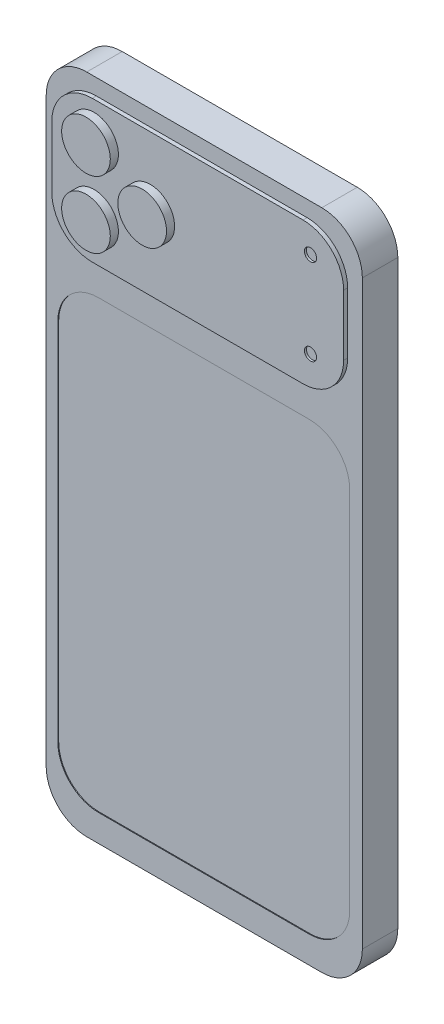
SolidWorks part; units mm, degrees
material "Plastique personnalisé"
ref_plane "Plan de face" through (0, 0, 0) normal (0, 0, 1) x (1, 0, 0)
ref_plane "Plan de dessus" through (0, 0, 0) normal (0, 1, 0) x (1, 0, 0)
ref_plane "Plan de droite" through (0, 0, 0) normal (1, 0, 0) x (0, 0, -1)
sketch "Esquisse2" plane through (0, 0, 0) normal (0, 0, 1) x (1, 0, 0)
  line L1 (10, 0) -> (68, 0)
  line L2 (0, 10) -> (0, 153.4)
  line L3 (10, 163.4) -> (68, 163.4)
  line L4 (78, 10) -> (78, 153.4)
  arc A0 (68, 0) -> (78, 10) centre (68, 10) ccw
  arc A1 (10, 0) -> (0, 10) centre (10, 10) cw
  arc A2 (0, 153.4) -> (10, 163.4) centre (10, 153.4) cw
  arc A3 (68, 163.4) -> (78, 153.4) centre (68, 153.4) cw
  point P7 (78, 0)
  point P10 (0, 0)
  point P13 (0, 163.4)
  dimension "D3" = 10
  dimension "D1" = 163.4
  dimension "D2" = 78
extrude "Boss.-Extru.1" add sketch "Esquisse2" along normal blind 8.75
sketch "Esquisse4" plane through (0, 0, 8.75) normal (0, 0, 1) x (1, 0, 0)
  line L1 (12.3759, 159.4654) -> (64.3759, 159.4654)
  line L2 (2.3759, 149.4654) -> (2.3759, 134.4654)
  line L3 (12.3759, 124.4654) -> (64.3759, 124.4654)
  line L4 (74.3759, 149.4654) -> (74.3759, 134.4654)
  arc A0 (64.3759, 124.4654) -> (74.3759, 134.4654) centre (64.3759, 134.4654) ccw
  arc A1 (64.3759, 159.4654) -> (74.3759, 149.4654) centre (64.3759, 149.4654) cw
  arc A2 (12.3759, 159.4654) -> (2.3759, 149.4654) centre (12.3759, 149.4654) ccw
  arc A3 (2.3759, 134.4654) -> (12.3759, 124.4654) centre (12.3759, 134.4654) ccw
  point P8 (74.3759, 159.4654)
  point P11 (2.3759, 159.4654)
  point P14 (2.3759, 124.4654)
  dimension "D3" = 10
  dimension "D1" = 72
  dimension "D2" = 35
extrude "Boss.-Extru.2" add sketch "Esquisse4" along normal blind 1
sketch "Esquisse5" plane through (0, 0, 9.75) normal (0, 0, 1) x (1, 0, 0)
  circle A0 centre (12.8176, 150.6803) radius 6
  circle A1 centre (26.6807, 142.2325) radius 6
  circle A2 centre (12.8176, 134.2179) radius 6
  dimension "D1" = 12
  dimension "D2" = 12
  dimension "D3" = 12
extrude "Boss.-Extru.3" add sketch "Esquisse5" along normal blind 2
sketch "Esquisse6" plane through (0, 0, 9.75) normal (0, 0, 1) x (1, 0, 0)
  circle A0 centre (66.2098, 152.9649) radius 1.5
  circle A1 centre (66.2098, 131.7454) radius 1.5
  dimension "D1" = 3
  dimension "D2" = 3
extrude "Enlèv. mat.-Extru.1" cut sketch "Esquisse6" against normal blind 0.5
ref_plane "Plan1" through (0, 10, 8.75) normal (0, -1, 0) x (-1, 0, 0)
sketch "Esquisse9" plane through (0, 0, 8.75) normal (0, 0, 1) x (1, 0, 0)
  line L1 (12.888, 116.6361) -> (64.888, 116.6361)
  line L2 (2.888, 106.6361) -> (2.888, 16.6361)
  line L3 (12.888, 6.6361) -> (64.888, 6.6361)
  line L4 (74.888, 106.6361) -> (74.888, 16.6361)
  arc A0 (64.888, 6.6361) -> (74.888, 16.6361) centre (64.888, 16.6361) ccw
  arc A1 (2.888, 16.6361) -> (12.888, 6.6361) centre (12.888, 16.6361) ccw
  arc A2 (12.888, 116.6361) -> (2.888, 106.6361) centre (12.888, 106.6361) ccw
  arc A3 (64.888, 116.6361) -> (74.888, 106.6361) centre (64.888, 106.6361) cw
  point P6 (74.888, 6.6361)
  point P9 (2.888, 6.6361)
  point P14 (74.888, 116.6361)
  dimension "D3" = 10
  dimension "D1" = 110
  dimension "D2" = 72
extrude "Enlèv. mat.-Extru.2" cut sketch "Esquisse9" against normal blind 0.2 contours L2 A1 L3 A0 L4 A3 L1 A2
